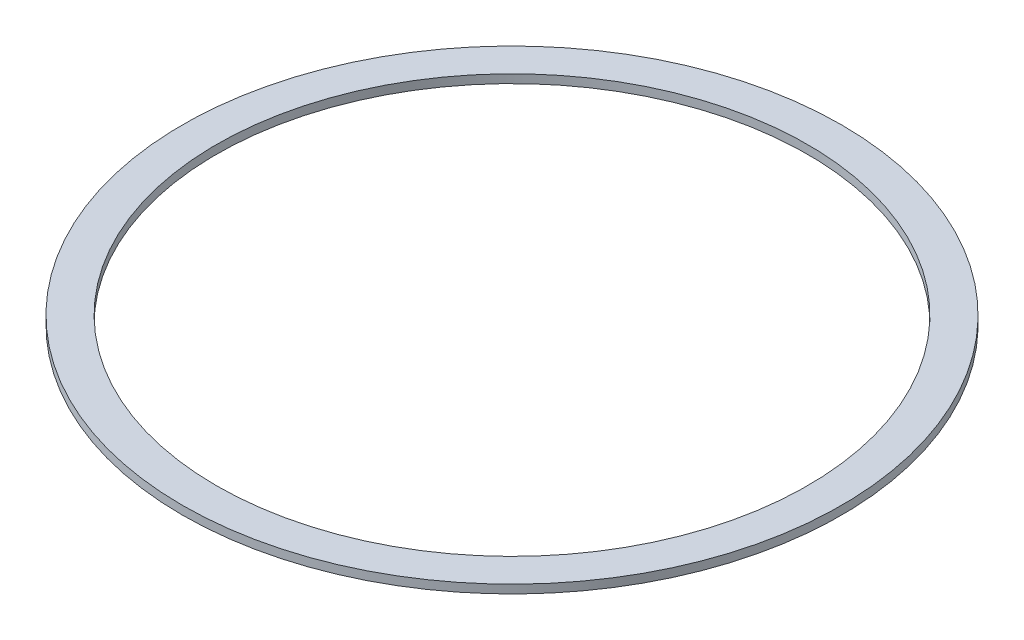
SolidWorks part; units mm, degrees
ref_plane "Front Plane" through (0, 0, 0) normal (0, 0, 1) x (1, 0, 0)
ref_plane "Top Plane" through (0, 0, 0) normal (0, 1, 0) x (1, 0, 0)
ref_plane "Right Plane" through (0, 0, 0) normal (1, 0, 0) x (0, 0, -1)
sketch "Sketch1" plane through (0, 0, 0) normal (0, 1, 0) x (1, 0, 0)
  circle A0 centre (0, 0) radius 34.75
  circle A1 centre (0, 0) radius 38.75
  dimension "D1" = 69.5
  dimension "D2" = 4
extrude "Boss-Extrude1" add sketch "Sketch1" along normal blind 1
